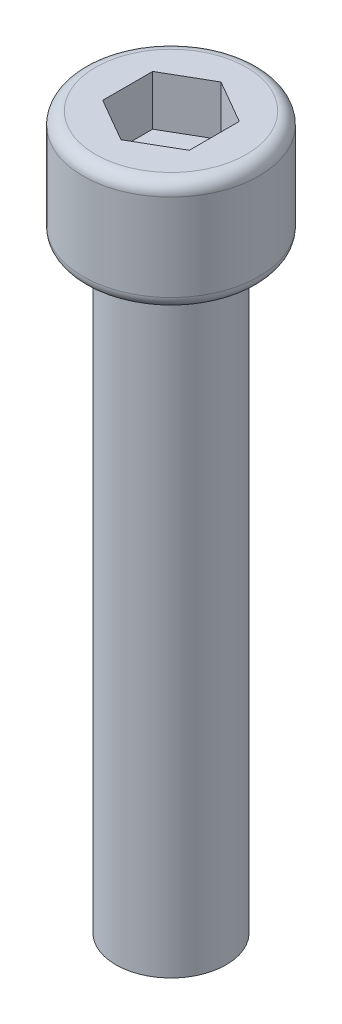
SolidWorks part; units mm, degrees
ref_plane "Front Plane" through (0, 0, 0) normal (0, 0, 1) x (1, 0, 0)
ref_plane "Top Plane" through (0, 0, 0) normal (0, 1, 0) x (1, 0, 0)
ref_plane "Right Plane" through (0, 0, 0) normal (1, 0, 0) x (0, 0, -1)
sketch "Sketch2" plane through (0, 0, 0) normal (0, 1, 0) x (1, 0, 0)
  circle A0 centre (0, 0) radius 2.794
  dimension "D1" = 5.588
extrude "Boss-Extrude1" add sketch "Sketch2" along normal blind 3.556
sketch "Sketch4" plane through (0, 0, 0) normal (0, -1, 0) x (1, 0, 0)
  circle A0 centre (0, 0) radius 1.7526
  dimension "D1" = 3.5052
extrude "Boss-Extrude2" add sketch "Sketch4" along normal blind 19.05
cosmetic thread "Cosmetic Thread1" parameters "D2"=2.5603
fillet "Fillet1" radius 0.3969 2 edges at (0, 0, 2.794) (0, 3.556, 2.794)
sketch "Sketch5" plane through (0, 3.556, 0) normal (0, 1, 0) x (1, 0, 0)
  line L1 (-1.3748, 0.7937) -> (-1.3748, -0.7937)
  line L2 (-1.3748, -0.7937) -> (0, -1.5875)
  line L3 (0, -1.5875) -> (1.3748, -0.7937)
  line L4 (1.3748, -0.7937) -> (1.3748, 0.7937)
  line L5 (1.3748, 0.7937) -> (0, 1.5875)
  line L6 (0, 1.5875) -> (-1.3748, 0.7937)
  circle A0 centre (0, 0) radius 1.3748 construction
  dimension "D1" = 1.5875
extrude "Cut-Extrude1" cut sketch "Sketch5" against normal blind 1.5875
